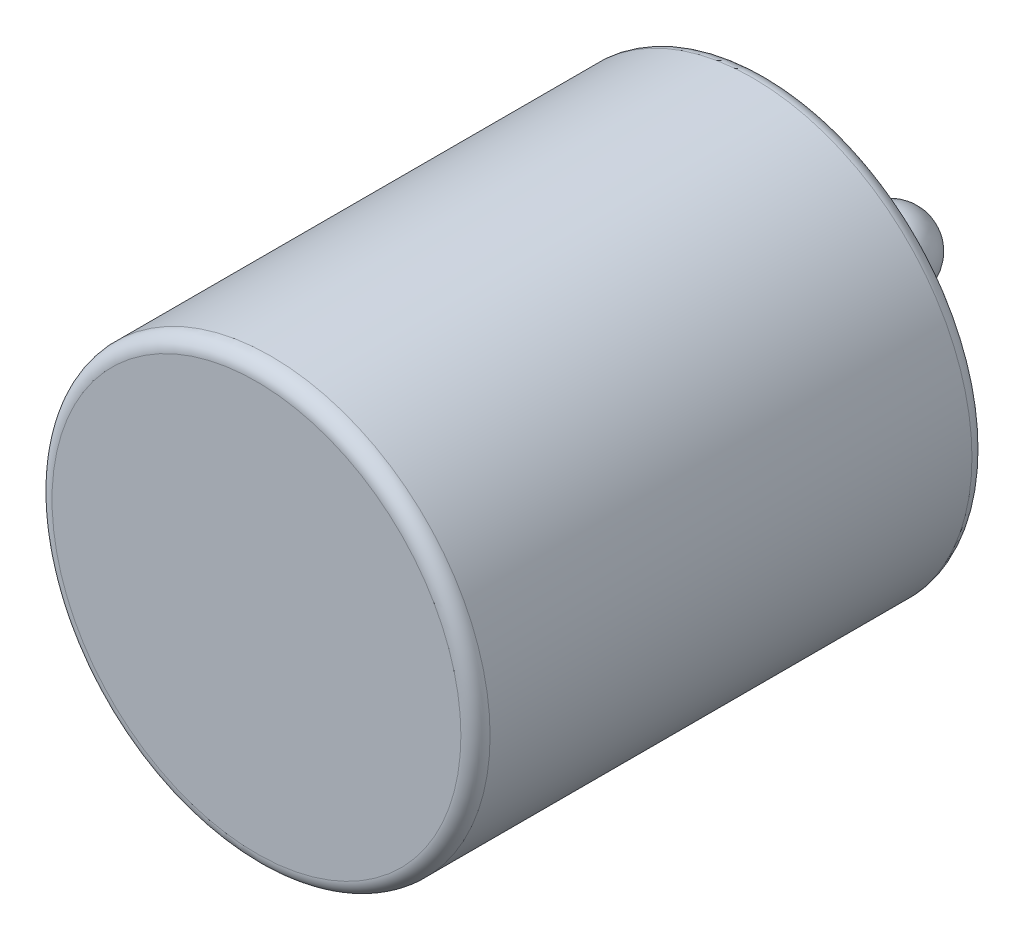
SolidWorks part; units mm, degrees
ref_plane "Front Plane" through (0, 0, 0) normal (0, 0, 1) x (1, 0, 0)
ref_plane "Top Plane" through (0, 0, 0) normal (0, 1, 0) x (1, 0, 0)
ref_plane "Right Plane" through (0, 0, 0) normal (1, 0, 0) x (0, 0, -1)
sketch "Sketch1" plane through (0, 0, 0) normal (0, 0, 1) x (1, 0, 0)
  circle A0 centre (0, 0) radius 3
  dimension "D1" = 6
extrude "Boss-Extrude1" add sketch "Sketch1" along normal blind 7
fillet "Fillet2" radius 0.2 1 edges at (3, 0, 7)
fillet "Fillet3" radius 0.2 1 edges at (3, 0, 0)
sketch "Sketch4" plane through (0, 0, 0) normal (0, 1, 0) x (1, 0, 0)
  line L0 (0, 5.422) -> (0, -10.0535) construction
  line L3 (0, 0) -> (2.8, 0)
  line L5 (2.8, 0) -> (0.3487, 1.3057)
  line L7 (0, 0) -> (0, 2.2)
  arc A1 (0.3487, 1.3057) -> (0, 2.2) centre (0, 1.6849) ccw
  point P10 (0, 2.2438)
  point P11 (0, 1.6849)
revolve "Revolve1" add sketch "Sketch4" angle 360 about L0
